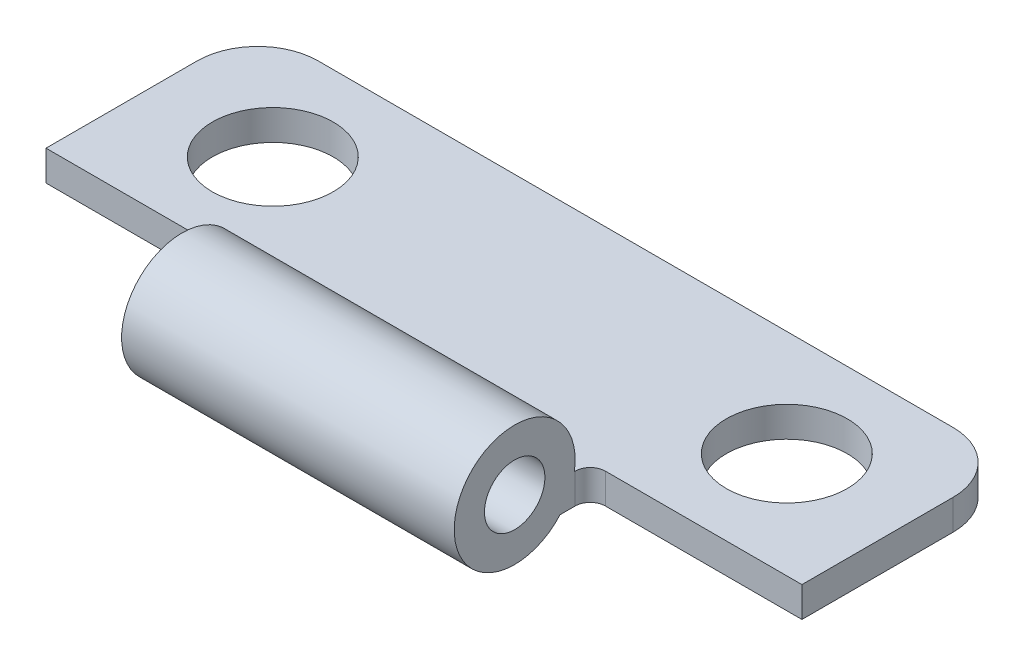
SolidWorks part; units mm, degrees
ref_plane "前视基准面" through (0, 0, 0) normal (0, 0, 1) x (1, 0, 0)
ref_plane "上视基准面" through (0, 0, 0) normal (0, 1, 0) x (1, 0, 0)
ref_plane "右视基准面" through (0, 0, 0) normal (1, 0, 0) x (0, 0, -1)
other "Configuration Table"
sketch "草图1" plane through (0, 0, 0) normal (0, 1, 0) x (1, 0, 0)
  line L0 (-12.5, 1) -> (-5.5, 1)
  line L1 (-12.5, 1) -> (-12.5, 8)
  line L2 (-12.5, 8) -> (12.5, 8)
  line L3 (12.5, 8) -> (12.5, 1)
  line L4 (-12.5, 4.5) -> (12.5, 4.5) construction
  line L5 (-5.5, 0) -> (5.5, 0)
  line L6 (5.5, 0) -> (5.5, 1)
  line L7 (-5.5, 0) -> (-5.5, 1)
  line L8 (5.5, 1) -> (12.5, 1)
  line L9 (0, 0) -> (0, 8) construction
  circle A0 centre (8.5, 4.5) radius 2
  circle A1 centre (-8.5, 4.5) radius 2
  point P14 (0, 0)
  dimension "D5" = 4
  dimension "D1" = 1
  dimension "D2" = 7
  dimension "D3" = 11
  dimension "D4" = 25
  dimension "D6" = 17
extrude "凸台-拉伸1" add sketch "草图1" along normal blind 1
fillet "圆角1" radius 2 2 edges at (-12.5, 0.5, -8) (12.5, 0.5, -8)
fillet "圆角2" radius 0.5 2 edges at (5.5, 0.5, -1) (-5.5, 0.5, -1)
sketch "草图3" plane through (0, 0, 0) normal (1, 0, 0) x (0, 0, -1)
  line L0 (1, 1) -> (1, 0) construction
  circle A0 centre (-1.5, 1.3229) radius 2
  circle A1 centre (-1.5, 1.3229) radius 1
  point P3 (-2.2914, 1.0887)
  point P4 (-1.2296, 1.6207)
  point P5 (-0.8247, 1.7671)
  point P6 (-1.5979, 1.7411)
  point P8 (-1.2836, 1.5338)
  dimension "D1" = 4
  dimension "D2" = 2
  dimension "D3" = 2.5
extrude "凸台-拉伸2" add sketch "草图3" along normal mid plane 11
